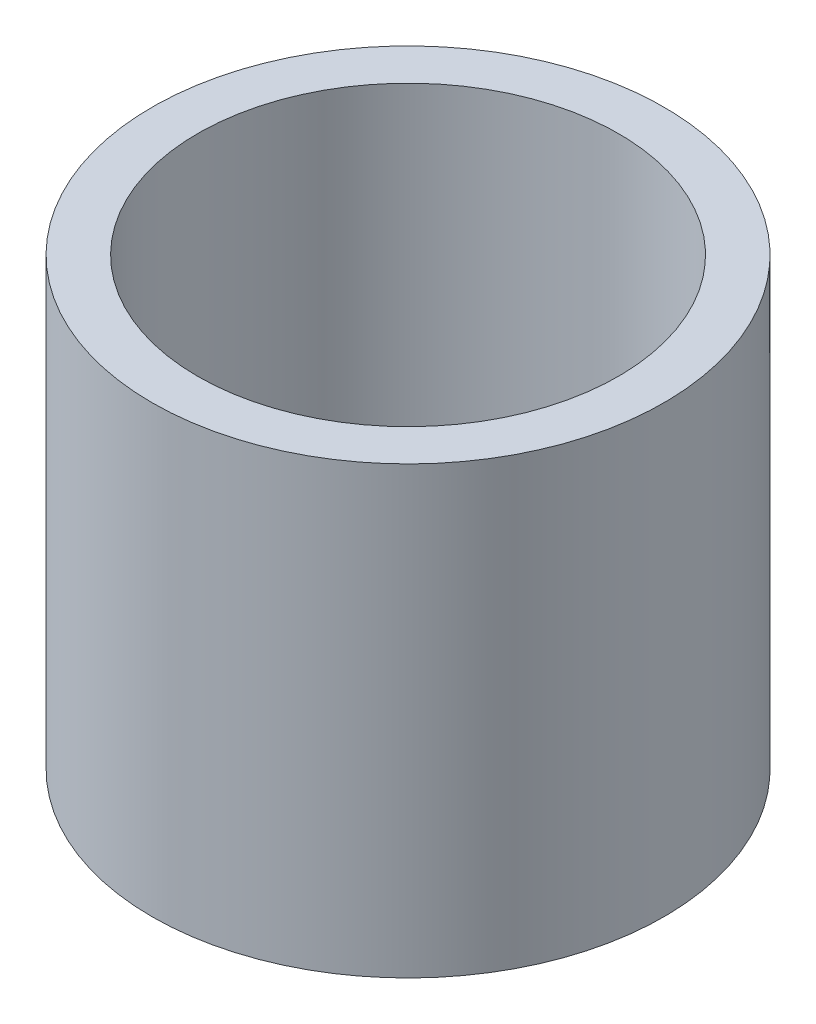
SolidWorks part; units mm, degrees
material "ｶﾞﾗｽ"
ref_plane "正面" through (0, 0, 0) normal (0, 0, 1) x (1, 0, 0)
ref_plane "平面" through (0, 0, 0) normal (0, 1, 0) x (1, 0, 0)
ref_plane "右側面" through (0, 0, 0) normal (1, 0, 0) x (0, 0, -1)
sketch "ｽｹｯﾁ1" plane through (0, 0, 0) normal (0, 1, 0) x (1, 0, 0)
  circle A0 centre (0, 0) radius 11.5
  dimension "D1" = 23
extrude "ﾎﾞｽ - 押し出し1" add sketch "ｽｹｯﾁ1" along normal blind 20
sketch "ｽｹｯﾁ2" plane through (0, 20, 0) normal (0, 1, 0) x (1, 0, 0)
  circle A0 centre (0, 0) radius 9.45
  dimension "D1" = 18.9
extrude "ｶｯﾄ - 押し出し1" cut sketch "ｽｹｯﾁ2" against normal through all
